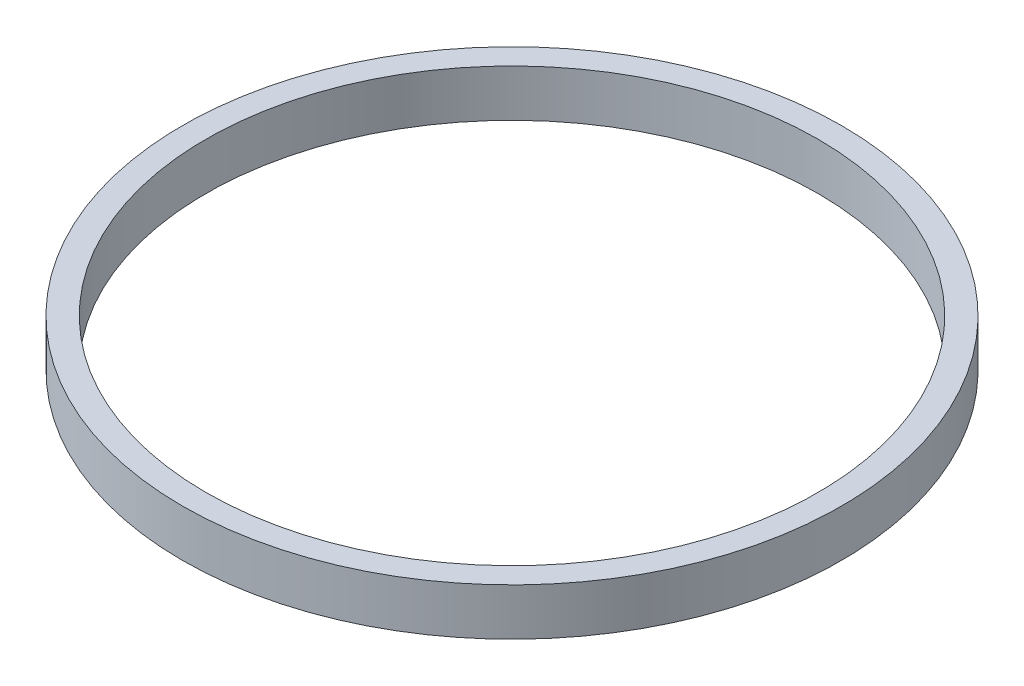
SolidWorks part; units mm, degrees
ref_plane "Спереди" through (0, 0, 0) normal (0, 0, 1) x (1, 0, 0)
ref_plane "Сверху" through (0, 0, 0) normal (0, 1, 0) x (1, 0, 0)
ref_plane "Справа" through (0, 0, 0) normal (1, 0, 0) x (0, 0, -1)
sketch "Эскиз1" plane through (0, 0, 0) normal (0, 1, 0) x (1, 0, 0)
  circle A0 centre (0, 0) radius 21
  circle A1 centre (0, 0) radius 19.5
  dimension "D1" = 42
  dimension "D2" = 39
extrude "Бобышка-Вытянуть1" add sketch "Эскиз1" along normal blind 3
